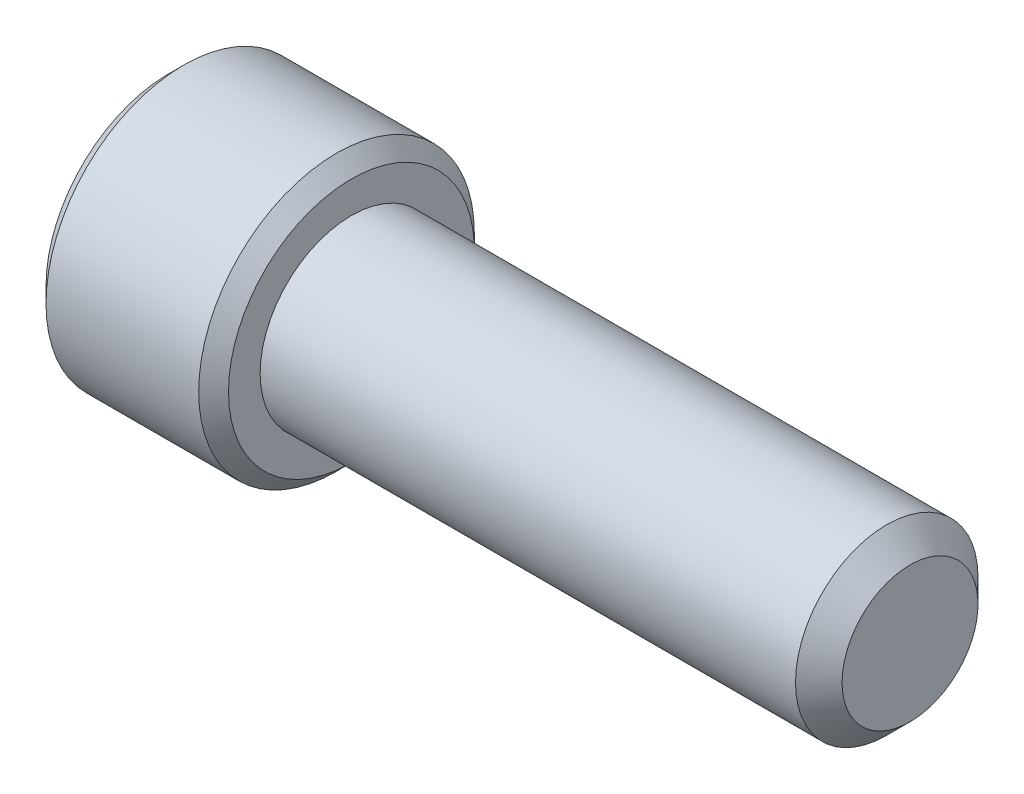
SolidWorks part; units mm, degrees
material "Galvanized Steel"
ref_plane "Front Plane" through (0, 0, 0) normal (0, 0, 1) x (1, 0, 0)
ref_plane "Top Plane" through (0, 0, 0) normal (0, 1, 0) x (1, 0, 0)
ref_plane "Right Plane" through (0, 0, 0) normal (1, 0, 0) x (0, 0, -1)
sketch "Sketch1" plane through (0, 0, 0) normal (0, 0, 1) x (1, 0, 0)
  line L0 (-124.8747, 0) -> (154.6144, 0) construction
  line L1 (0, 97.9574) -> (0, -96.1406) construction
  line L2 (12.6365, 0) -> (12.6365, 2.3178)
  line L3 (12.6365, 2.3178) -> (11.8428, 3.1115)
  line L4 (11.8428, 3.1115) -> (-6.4135, 3.1115)
  line L5 (-6.4135, 3.1115) -> (-6.4135, 4.191)
  line L6 (-6.9215, 4.699) -> (-12.1285, 4.699)
  line L7 (-12.6365, 4.191) -> (-12.6365, 0)
  line L8 (-12.6365, 0) -> (12.6365, 0)
  line L9 (-6.4135, 4.191) -> (-6.9215, 4.699)
  line L10 (-12.1285, 4.699) -> (-12.6365, 4.191)
  point P9 (-6.4135, 4.699)
  point P10 (-12.6365, 4.699)
  dimension "D1" = 9.398
  dimension "D2" = 6.223
  dimension "D3" = 6.223
  dimension "D4" = 19.05
  dimension "D5" = 45
  dimension "D6" = 0.7937
  dimension "D10" = 0.508
  dimension "D11" = 0.508
revolve "Revolve1" add sketch "Sketch1" angle 360 about L0
sketch "Sketch2" plane through (-12.6365, 0, 0) normal (-1, 0, 0) x (0, 0, 1)
  line L0 (0, 5.0398) -> (0, -5.3552) construction
  line L1 (-5.6471, 0) -> (6.1045, 0) construction
  line L2 (0, 2.7496) -> (-2.3812, 1.3748)
  line L3 (-2.3812, 1.3748) -> (-2.3812, -1.3748)
  line L4 (-2.3812, -1.3748) -> (0, -2.7496)
  line L5 (0, -2.7496) -> (2.3812, -1.3748)
  line L6 (2.3812, -1.3748) -> (2.3812, 1.3748)
  line L7 (2.3812, 1.3748) -> (0, 2.7496)
  dimension "D1" = 5.4993
  dimension "D2" = 4.7625
  dimension "D3" = 2.7496
extrude "Extrude1" cut sketch "Sketch2" against normal blind 3.81
